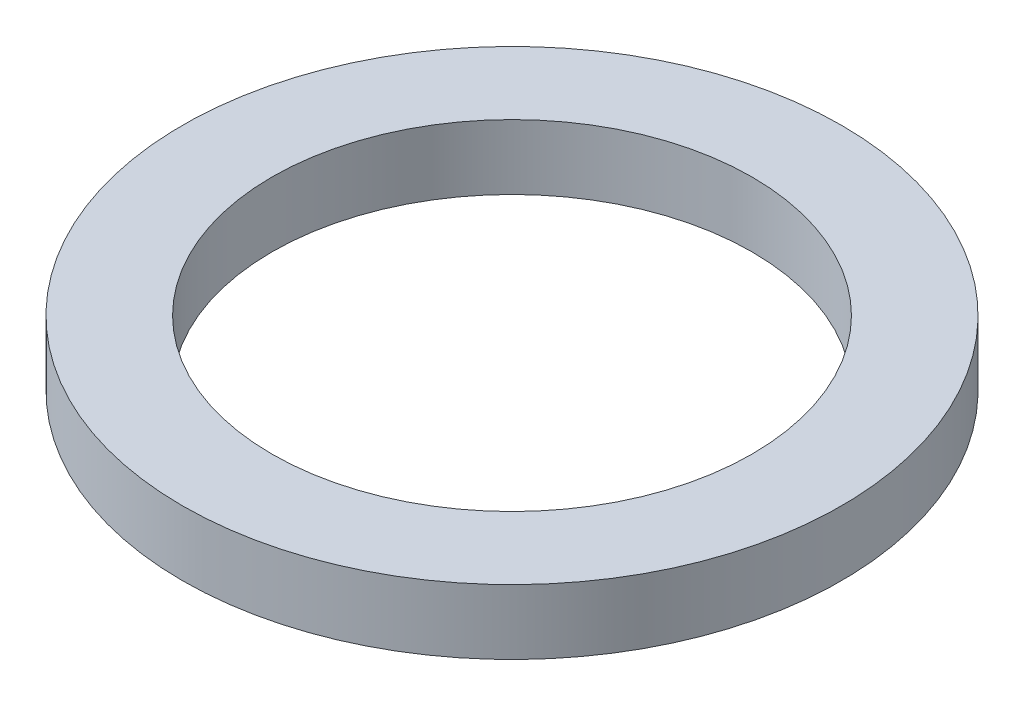
SolidWorks part; units mm, degrees
ref_plane "Front Plane" through (0, 0, 0) normal (0, 0, 1) x (1, 0, 0)
ref_plane "Top Plane" through (0, 0, 0) normal (0, 1, 0) x (1, 0, 0)
ref_plane "Right Plane" through (0, 0, 0) normal (1, 0, 0) x (0, 0, -1)
sketch "Sketch1" plane through (0, 0, 0) normal (0, 1, 0) x (1, 0, 0)
  circle A0 centre (0, 0) radius 25.4
  circle A1 centre (0, 0) radius 18.5
  dimension "D1" = 50.8
  dimension "D2" = 37
extrude "Boss-Extrude1" add sketch "Sketch1" along normal blind 5
